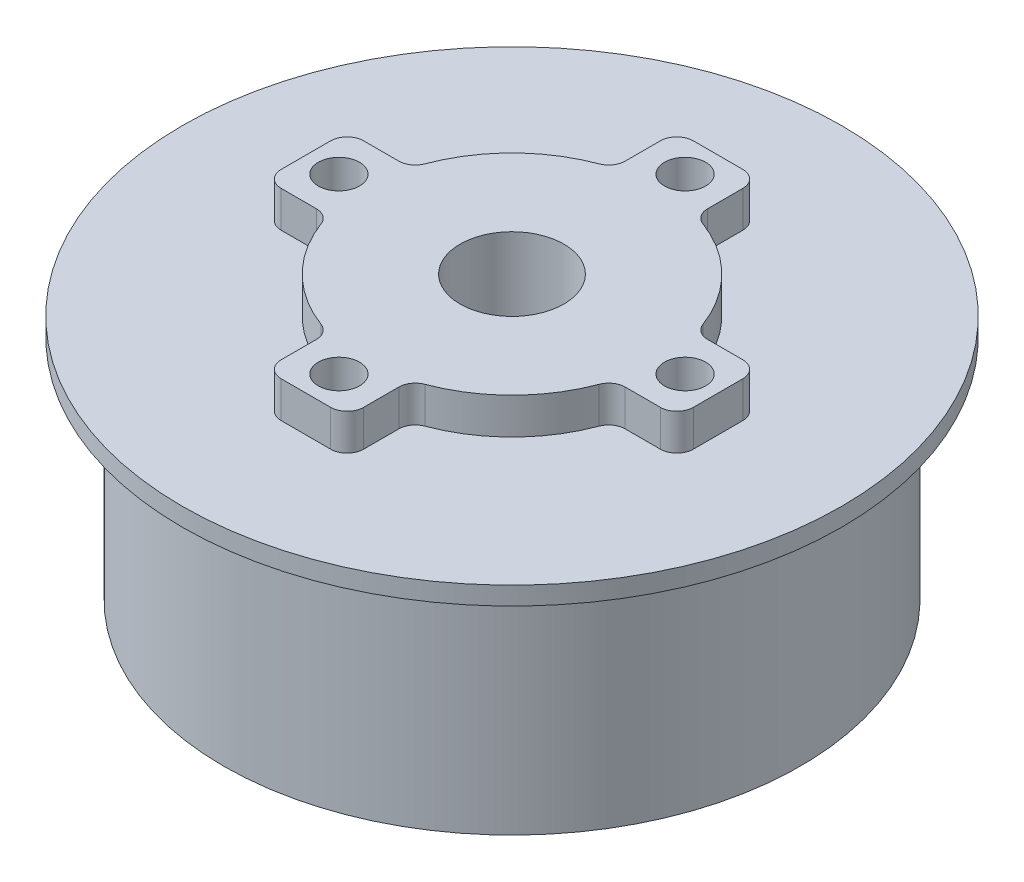
SolidWorks part; units mm, degrees
material "Alumina"
ref_plane "Front Plane" through (0, 0, 0) normal (0, 0, 1) x (1, 0, 0)
ref_plane "Top Plane" through (0, 0, 0) normal (0, 1, 0) x (1, 0, 0)
ref_plane "Right Plane" through (0, 0, 0) normal (1, 0, 0) x (0, 0, -1)
sketch "Sketch1" plane through (0, 0, 0) normal (0, 1, 0) x (1, 0, 0)
  circle A0 centre (0, 0) radius 35
  dimension "D1" = 70
extrude "Boss-Extrude1" add sketch "Sketch1" along normal blind 27.6
sketch "Sketch2" plane through (0, 27.6, 0) normal (0, 1, 0) x (1, 0, 0)
  circle A0 centre (0, 0) radius 40
  dimension "D1" = 80
extrude "Boss-Extrude2" add sketch "Sketch2" along normal blind 2.2
sketch "Sketch3" plane through (0, 29.8, 0) normal (0, 1, 0) x (1, 0, 0)
  line L0 (-25, 5) -> (-17.2916, 5)
  line L1 (25, 5) -> (25, -5)
  line L2 (25, -5) -> (17.2916, -5)
  line L3 (-25, -5) -> (-25, 5)
  line L4 (-5, 25) -> (-5, 17.2916)
  line L5 (-5, -25) -> (5, -25)
  line L6 (5, -25) -> (5, -17.2916)
  line L7 (5, 25) -> (-5, 25)
  line L9 (17.2916, 5) -> (25, 5)
  line L10 (-17.2916, -5) -> (-25, -5)
  line L12 (5, 17.2916) -> (5, 25)
  line L14 (-5, -17.2916) -> (-5, -25)
  arc A0 (-17.2916, -5) -> (-5, -17.2916) centre (0, 0) ccw
  arc A1 (17.2916, 5) -> (5, 17.2916) centre (0, 0) ccw
  arc A2 (-5, 17.2916) -> (-17.2916, 5) centre (0, 0) ccw
  arc A3 (5, -17.2916) -> (17.2916, -5) centre (0, 0) ccw
  point P8 (-25, 0)
  point P11 (0, -25)
  dimension "D1" = 36
  dimension "D2" = 10
  dimension "D3" = 50
  dimension "D4" = 50
  dimension "D5" = 10
extrude "Boss-Extrude3" add sketch "Sketch3" along normal blind 4.4
fillet "Fillet3" radius 2 16 edges at (-25, 32, -5) (-17.2916, 32, -5) (-5, 32, -17.2916) (-5, 32, -25) (5, 32, -25) (5, 32, -17.2916) (17.2916, 32, -5) (25, 32, -5) (25, 32, 5) (17.2916, 32, 5) (5, 32, 17.2916) (5, 32, 25) (-5, 32, 25) (-5, 32, 17.2916) (-17.2916, 32, 5) (-25, 32, 5)
sketch "Sketch4" plane through (0, 34.2, 0) normal (0, 1, 0) x (1, 0, 0)
  circle A0 centre (0, 0) radius 6.3
  dimension "D1" = 12.6
extrude "Cut-Extrude1" cut sketch "Sketch4" against normal up to surface (34.2 mm away) up to face at (0, 0, 35)
sketch "Sketch5" plane through (0, 34.2, 0) normal (0, 1, 0) x (1, 0, 0)
  circle A0 centre (21, 0) radius 2.5
  circle A1 centre (0, -21) radius 2.5
  circle A2 centre (-21, 0) radius 2.5
  circle A3 centre (0, 21) radius 2.5
  point P12 (0, 0)
  dimension "D2" = 5
  dimension "D1" = 21
  dimension "D3" = 4
extrude "Cut-Extrude2" cut sketch "Sketch5" against normal up to surface (4.4 mm away) up to face at (0, 29.8, 0)
equation "\"27.6mmmm\"=10"
